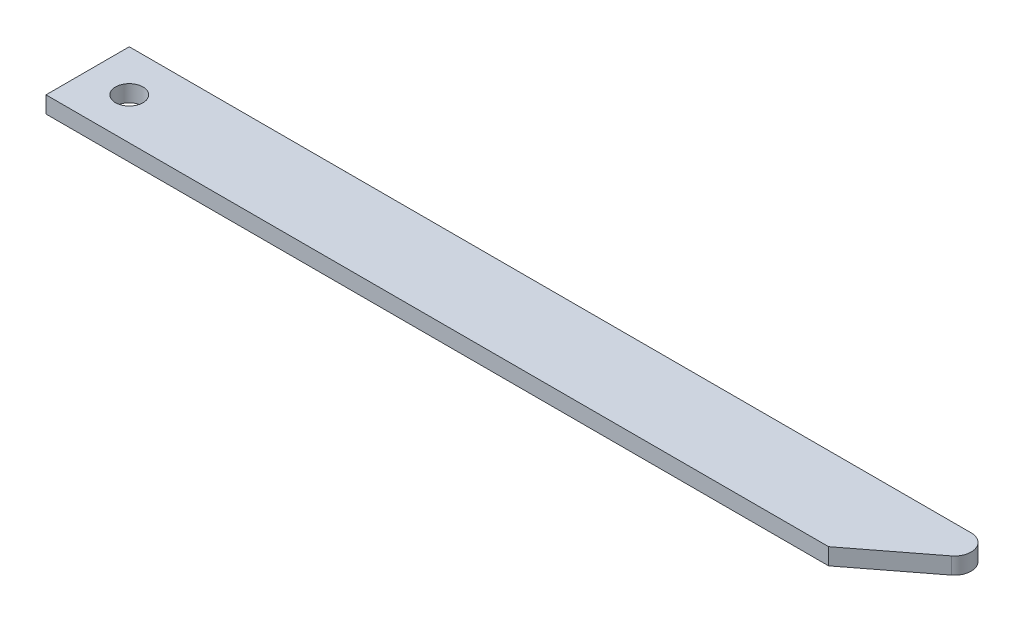
SolidWorks part; units mm, degrees
ref_plane "Front Plane" through (0, 0, 0) normal (0, 0, 1) x (1, 0, 0)
ref_plane "Top Plane" through (0, 0, 0) normal (0, 1, 0) x (1, 0, 0)
ref_plane "Right Plane" through (0, 0, 0) normal (1, 0, 0) x (0, 0, -1)
sketch "Sketch1" plane through (0, 0, 0) normal (0, 1, 0) x (1, 0, 0)
  line L1 (0, 0) -> (-119.38, 0)
  line L4 (-119.38, 0) -> (-119.38, 12.7)
  line L10 (10.5908, 8.1467) -> (0, 0)
  line L11 (-119.38, 12.7) -> (9.0421, 12.7)
  arc A0 (9.0421, 12.7) -> (10.5908, 8.1467) centre (9.0421, 10.16) cw
  point P8 (16.51, 12.7)
  dimension "D3" = 2.54
  dimension "D1" = 119.38
  dimension "D2" = 12.7
  dimension "D4" = 135.89
extrude "Boss-Extrude1" add sketch "Sketch1" along normal blind 2.54
sketch "Sketch4" plane through (0, 2.54, 0) normal (0, 1, 0) x (1, 0, 0)
  line L0 (-119.38, 12.7) -> (-119.38, 0) construction
  line L1 (-119.38, 0) -> (0, 0) construction
  circle A0 centre (-113.03, 6.35) radius 2.0955
  dimension "D1" = 4.191
  dimension "D2" = 6.35
  dimension "D3" = 6.35
extrude "Cut-Extrude2" cut sketch "Sketch4" against normal through all
